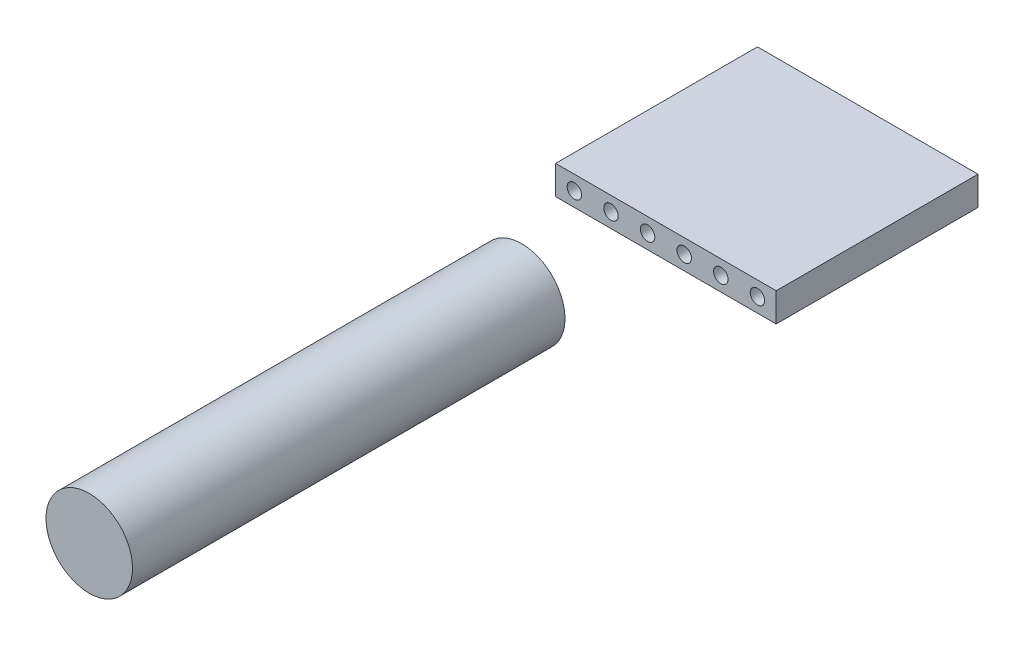
SolidWorks part; units mm, degrees
ref_plane "Plan de face" through (0, 0, 0) normal (0, 0, 1) x (1, 0, 0)
ref_plane "Plan de dessus" through (0, 0, 0) normal (0, 1, 0) x (1, 0, 0)
ref_plane "Plan de droite" through (0, 0, 0) normal (1, 0, 0) x (0, 0, -1)
sketch "Esquisse1" plane through (0, 0, 0) normal (0, 0, 1) x (1, 0, 0)
  line L1 (0, 1) -> (15.3, 1)
  line L2 (0, 1) -> (0, -1)
  line L3 (0, -1) -> (15.3, -1)
  line L4 (15.3, 1) -> (15.3, -1)
  circle A0 centre (1.3, 0) radius 0.5
  circle A1 centre (3.84, 0) radius 0.5
  circle A2 centre (6.38, 0) radius 0.5
  circle A3 centre (8.92, 0) radius 0.5
  circle A4 centre (11.46, 0) radius 0.5
  circle A5 centre (14, 0) radius 0.5
  dimension "D4" = 1.3
  dimension "D3" = 1.3
  dimension "D1" = 2
  dimension "D2" = 1
  dimension "D5" = 6
extrude "Boss.-Extru.1" add sketch "Esquisse1" along normal blind 14
sketch "Esquisse2" plane through (0, 0, 14) normal (0, 0, 1) x (1, 0, 0)
  circle A0 centre (7.65, 2) radius 3
extrude "Boss.-Extru.2" add sketch "Esquisse2" along normal blind 40
sketch "Esquisse3" plane through (0, 0, 14) normal (0, 0, -1) x (-1, 0, 0)
  circle A0 centre (-7.65, 2) radius 4
extrude "Enlèv. mat.-Extru.1" cut sketch "Esquisse3" against normal blind 10
